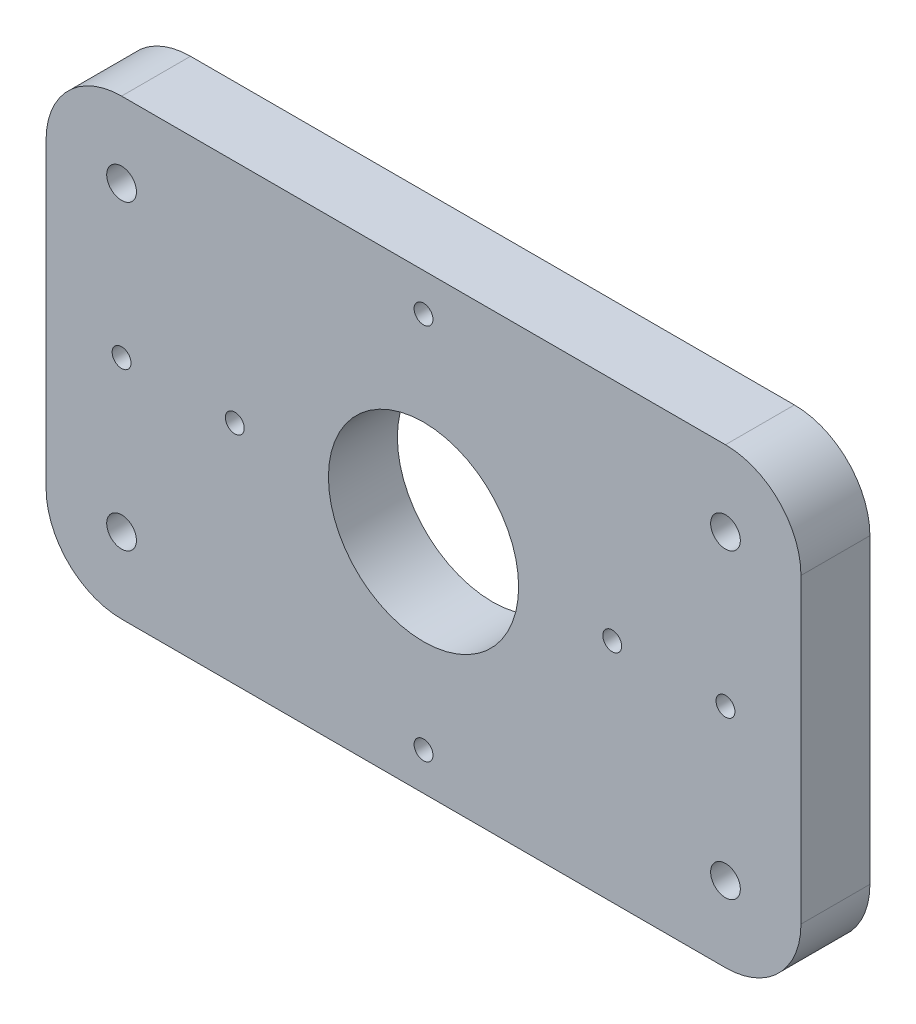
SolidWorks part; units mm, degrees
material "Acrylic (Medium-high impact)"
ref_plane "Front Plane" through (0, 0, 0) normal (0, 0, 1) x (1, 0, 0)
ref_plane "Top Plane" through (0, 0, 0) normal (0, 1, 0) x (1, 0, 0)
ref_plane "Right Plane" through (0, 0, 0) normal (1, 0, 0) x (0, 0, -1)
sketch "Sketch1" plane through (0, 0, 0) normal (0, 0, 1) x (1, 0, 0)
  line L1 (0, 0) -> (-38.1, 0)
  line L2 (0, 0) -> (0, 38.1)
  line L3 (0, 38.1) -> (-38.1, 38.1)
  line L4 (-38.1, 0) -> (-38.1, 38.1)
  dimension "D1" = 38.1
extrude "Boss-Extrude1" add sketch "Sketch1" along normal blind 5.8
sketch "Sketch2" plane through (0, 0, 5.8) normal (0, 0, 1) x (1, 0, 0)
  line L0 (-19.05, 19.05) -> (-38.1, 19.05) construction
  line L1 (-38.1, 38.1) -> (-38.1, 0) construction
  line L2 (-19.05, 19.05) -> (-19.05, 0) construction
  line L3 (-38.1, 0) -> (0, 0) construction
  circle A0 centre (-19.05, 19.05) radius 8
  dimension "D1" = 16
extrude "Cut-Extrude1" cut sketch "Sketch2" against normal blind 12.7
sketch "Sketch4" plane through (0, 0, 5.8) normal (0, 0, 1) x (1, 0, 0)
  line L0 (-19.05, 38.1) -> (-19.05, 0) construction
  line L1 (0, 38.1) -> (-38.1, 38.1) construction
  line L2 (-38.1, 0) -> (0, 0) construction
  line L3 (-19.05, 19.05) -> (-38.1, 19.05) construction
  line L4 (-38.1, 38.1) -> (-38.1, 0) construction
  circle A0 centre (-34.925, 19.05) radius 0.7937
  circle A1 centre (-19.05, 34.925) radius 0.7937
  circle A2 centre (-3.175, 19.05) radius 0.7938
  circle A3 centre (-19.05, 3.175) radius 0.7937
  dimension "D2" = 1.5875
  dimension "D1" = 3.175
  dimension "D3" = 4
extrude "Cut-Extrude3" cut sketch "Sketch4" against normal through all
sketch "Sketch6" plane through (0, 0, 5.8) normal (0, 0, 1) x (1, 0, 0)
  line L0 (0, 38.1) -> (-38.1, 38.1) construction
  line L1 (0, 0) -> (12.7, 0)
  line L2 (0, 0) -> (0, 38.1)
  line L3 (0, 38.1) -> (12.7, 38.1)
  line L4 (12.7, 0) -> (12.7, 38.1)
  line L5 (-19.05, 0) -> (-19.05, 38.1) construction
  line L6 (-38.1, 0) -> (0, 0) construction
  line L7 (-50.8, 0) -> (-50.8, 38.1)
  line L8 (-38.1, 38.1) -> (-50.8, 38.1)
  line L9 (-38.1, 0) -> (-38.1, 38.1)
  line L10 (-38.1, 0) -> (-50.8, 0)
  dimension "D1" = 12.7
extrude "Boss-Extrude2" add sketch "Sketch6" against normal through all
hole_wizard "M3x0.5 Tapped Hole1" positions "Sketch8" profile "Sketch7" tap size "M3x0.5" standard "ANSI Metric"
sketch "Sketch8" plane through (0, 0, 5.8) normal (0, 0, 1) x (1, 0, 0)
  line L0 (-44.45, 38.1) -> (-44.45, 0) construction
  line L1 (12.7, 38.1) -> (-50.8, 38.1) construction
  line L2 (-50.8, 0) -> (12.7, 0) construction
  line L4 (-50.8, 31.75) -> (12.7, 31.75) construction
  line L5 (-50.8, 38.1) -> (-50.8, 0) construction
  line L6 (12.7, 0) -> (12.7, 38.1) construction
  line L7 (-50.8, 19.05) -> (12.7, 19.05) construction
  line L9 (-19.05, 38.1) -> (-19.05, 0) construction
  line L10 (12.7, 38.1) -> (-50.8, 38.1) construction
  line L11 (-50.8, 0) -> (12.7, 0) construction
  point P0 (-44.45, 31.75)
  point P39 (6.35, 31.75)
  point P41 (6.35, 6.35)
  point P42 (-44.45, 6.35)
  dimension "D1" = 6.35
  dimension "D2" = 6.35
sketch "Sketch7" plane through (-44.45, 31.75, 5.8) normal (1, 0, 0) x (0, -1, 0)
  line L0 (0, 0) -> (0, 8.2511)
  line L1 (0, 8.2511) -> (1.25, 7.5)
  line L2 (1.25, 7.5) -> (1.25, 0)
  line L5 (1.25, 0) -> (0, 0)
  line L10 (0, 8.2511) -> (-1.25, 7.5) construction
  line L11 (0, -6.35) -> (0, 107.95) construction
  dimension "Tap Drill Dia." = 2.5
  dimension "Tap Drill Depth" = 7.5
  dimension "Drill Angle" = 118
sketch "Sketch9" plane through (0, 0, 5.8) normal (0, 0, 1) x (1, 0, 0)
  line L0 (-44.45, 31.75) -> (-44.45, 6.35) construction
  line L1 (6.35, 31.75) -> (6.35, 6.35) construction
  circle A0 centre (-44.45, 19.05) radius 0.7937
  circle A1 centre (6.35, 19.05) radius 0.7938
  dimension "D1" = 1.5875
extrude "Cut-Extrude4" cut sketch "Sketch9" against normal through all
fillet "Fillet1" radius 6.35 4 edges at (12.7, 0, 2.9) (12.7, 38.1, 2.9) (-50.8, 0, 2.9) (-50.8, 38.1, 2.9)
other "Move Face1" [suppressed] parameters "D1"=0.2
